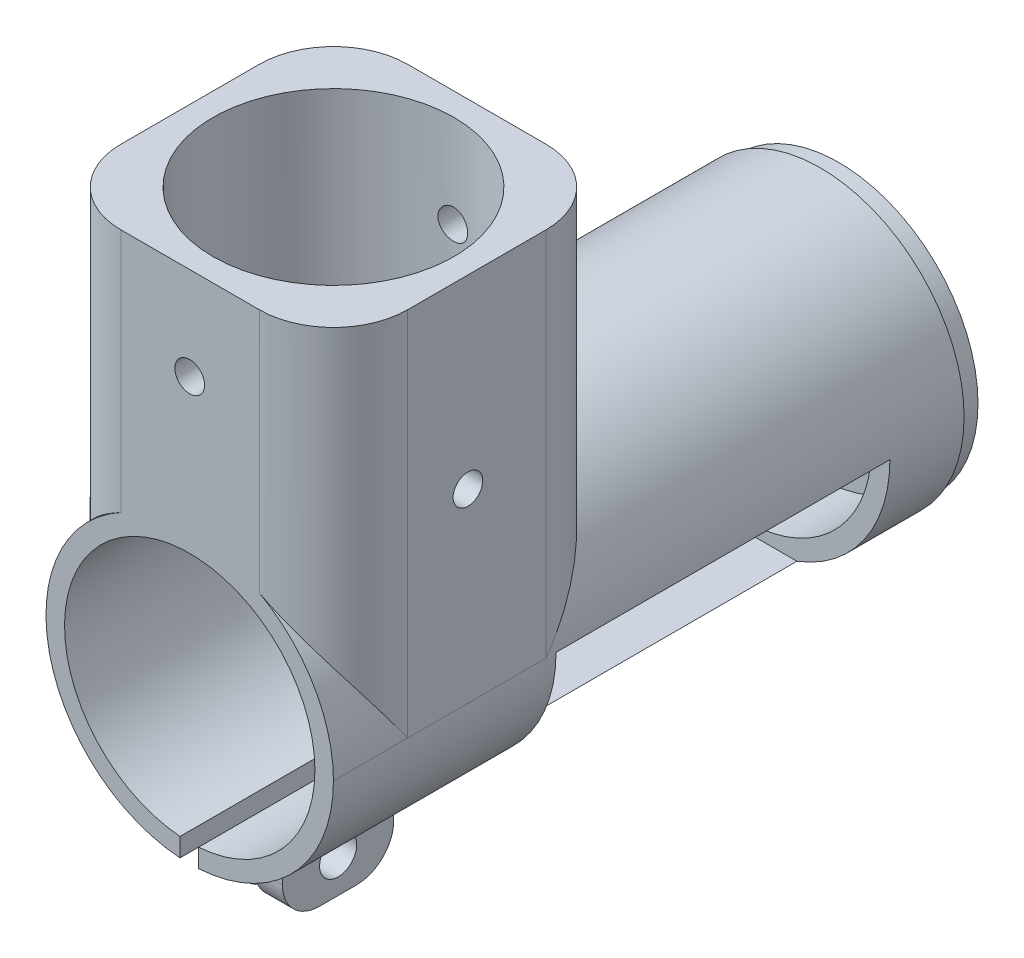
SolidWorks part; units mm, degrees
ref_plane "Front" through (0, 0, 0) normal (0, 0, 1) x (1, 0, 0)
ref_plane "Top" through (0, 0, 0) normal (0, 1, 0) x (1, 0, 0)
ref_plane "Right" through (0, 0, 0) normal (1, 0, 0) x (0, 0, -1)
sketch "Эскиз1" plane through (0, 0, 0) normal (0, 0, 1) x (1, 0, 0)
  circle A0 centre (0, 0) radius 13.5
  circle A1 centre (0, 0) radius 15.5
extrude "Бобышка-Вытянуть1" add sketch "Эскиз1" along normal blind 68
sketch "Эскиз2" plane through (0, 0, 0) normal (0, 0, -1) x (-1, 0, 0)
  circle A0 centre (0, 0) radius 15
  circle A2 centre (8.5, 0) radius 1.6
  circle A3 centre (-8.5, 0) radius 1.6
  circle A4 centre (0, 0) radius 5
extrude "Бобышка-Вытянуть2" add sketch "Эскиз2" along normal blind 2
sketch "Эскиз3" plane through (0, 0, 0) normal (0, 1, 0) x (1, 0, 0)
  line L2 (-7.4174, -37.0826) -> (7.5, -37.0826)
  line L3 (-15.4174, -45.0826) -> (-15.4174, -60)
  line L4 (-7.4174, -68) -> (7.5, -68)
  line L5 (15.5, -45.0826) -> (15.5, -60)
  line L6 (-15.4174, -37.0826) -> (15.5, -68) construction
  line L7 (-15.4174, -68) -> (15.5, -37.0826) construction
  circle A3 centre (0.0413, -52.5413) radius 13
  arc A4 (-15.4174, -60) -> (-7.4174, -68) centre (-7.4174, -60) ccw
  arc A5 (7.5, -68) -> (15.5, -60) centre (7.5, -60) ccw
  arc A6 (7.5, -37.0826) -> (15.5, -45.0826) centre (7.5, -45.0826) cw
  arc A7 (-7.4174, -37.0826) -> (-15.4174, -45.0826) centre (-7.4174, -45.0826) ccw
  dimension "D1" = 8
extrude "Бобышка-Вытянуть3" add sketch "Эскиз3" along normal blind 40
sketch "Эскиз4" plane through (0, 0, 68) normal (0, 0, 1) x (1, 0, 0)
  circle A0 centre (0, 0) radius 12.5
extrude "Вырез-Вытянуть1" cut sketch "Эскиз4" against normal blind 40
sketch "Эскиз5" plane through (0, 0, 0) normal (0, 0, 1) x (1, 0, 0)
  circle A1 centre (0, 30) radius 1.6
extrude "Вырез-Вытянуть4" cut sketch "Эскиз5" along normal through all
sketch "Эскиз6" plane through (0, 0, 0) normal (1, 0, 0) x (0, 0, -1)
  circle A1 centre (-53.5, 20) radius 1.6
extrude "Вырез-Вытянуть5" cut sketch "Эскиз6" against normal blind 40 and the other way blind 40
sketch "Эскиз7" plane through (0, 0, 0) normal (1, 0, 0) x (0, 0, -1)
  line L1 (-8, -14.5) -> (-44, -14.5)
  line L2 (-8, -14.5) -> (-8, 0)
  line L3 (-8, 0) -> (-44, 0)
  line L4 (-44, -14.5) -> (-44, 0)
extrude "Вырез-Вытянуть6" cut sketch "Эскиз7" against normal through all and the other way through all
sketch "Эскиз8" plane through (0, 0, 68) normal (0, 0, 1) x (1, 0, 0)
  line L1 (-1.0471, -10.2054) -> (0.9529, -10.2054)
  line L2 (-1.0471, -10.2054) -> (-1.0471, -20.7945)
  line L3 (-1.0471, -20.7945) -> (0.9529, -20.7945)
  line L4 (0.9529, -10.2054) -> (0.9529, -20.7945)
  line L5 (-1.0471, -10.2054) -> (0.9529, -20.7945) construction
  line L6 (-1.0471, -20.7945) -> (0.9529, -10.2054) construction
  arc A0 (-7.4174, 13.61) -> (7.5, 13.5647) centre (0, 0) ccw construction
  point P0 (-0.0471, -15.4999)
extrude "Вырез-Вытянуть7" cut sketch "Эскиз8" against normal blind 40
ref_plane "Плоскость1" through (0, 0, 56) normal (0, 0, -1) x (-1, 0, 0)
sketch "Эскиз9" plane through (0, 0, 56) normal (0, 0, -1) x (-1, 0, 0)
  line L5 (1.0471, -13.4593) -> (5, -13.4593)
  line L6 (1.0471, -13.4593) -> (1.0471, -22.4599)
  line L7 (1.0471, -22.4599) -> (5, -22.4599)
  line L8 (5, -13.4593) -> (5, -22.4599)
  line L9 (-0.9529, -13.4663) -> (-4, -13.4663)
  line L10 (-0.9529, -13.4663) -> (-0.9529, -22.4599)
  line L11 (-0.9529, -22.4599) -> (-4, -22.4599)
  line L12 (-4, -13.4663) -> (-4, -22.4599)
extrude "Бобышка-Вытянуть4" add sketch "Эскиз9" along normal blind 6 and the other way blind 6
sketch "Эскиз10" plane through (4, 0, 0) normal (1, 0, 0) x (0, 0, -1)
  line L0 (-62, -14.975) -> (-50, -22.4599) construction
  circle A0 centre (-56, -18.7175) radius 2
extrude "Вырез-Вытянуть8" cut sketch "Эскиз10" against normal through all
sketch "Эскиз11" plane through (-5, 0, 0) normal (-1, 0, 0) x (0, 0, 1)
  line L1 (60.0415, -18.7175) -> (58.0207, -15.2175)
  line L2 (58.0207, -15.2175) -> (53.9793, -15.2175)
  line L3 (53.9793, -15.2175) -> (51.9585, -18.7175)
  line L4 (51.9585, -18.7175) -> (53.9793, -22.2175)
  line L5 (53.9793, -22.2175) -> (58.0207, -22.2175)
  line L6 (58.0207, -22.2175) -> (60.0415, -18.7175)
  circle A0 centre (56, -18.7175) radius 3.5 construction
extrude "Вырез-Вытянуть9" cut sketch "Эскиз11" against normal blind 2
fillet "Скругление1" radius 4 4 edges at (-3.0235, -22.4599, 50) (-3.0235, -22.4599, 62) (2.4765, -22.4599, 62) (2.4765, -22.4599, 50)
sketch "Эскиз12" plane through (0, 40, 0) normal (0, 1, 0) x (1, 0, 0)
  line L0 (0.0413, -65.5413) -> (0.0413, -68) construction
  line L1 (-7.4174, -68) -> (7.5, -68) construction
  circle A0 centre (0.0413, -52.5413) radius 13 construction
sketch "Эскиз13" plane through (0, 0, 68) normal (0, 0, 1) x (1, 0, 0)
  circle A0 centre (0, 0) radius 13.5
extrude "Вырез-Вытянуть10" cut sketch "Эскиз13" against normal up to surface (68 mm away) up to face at (6.9, 0, 0)
